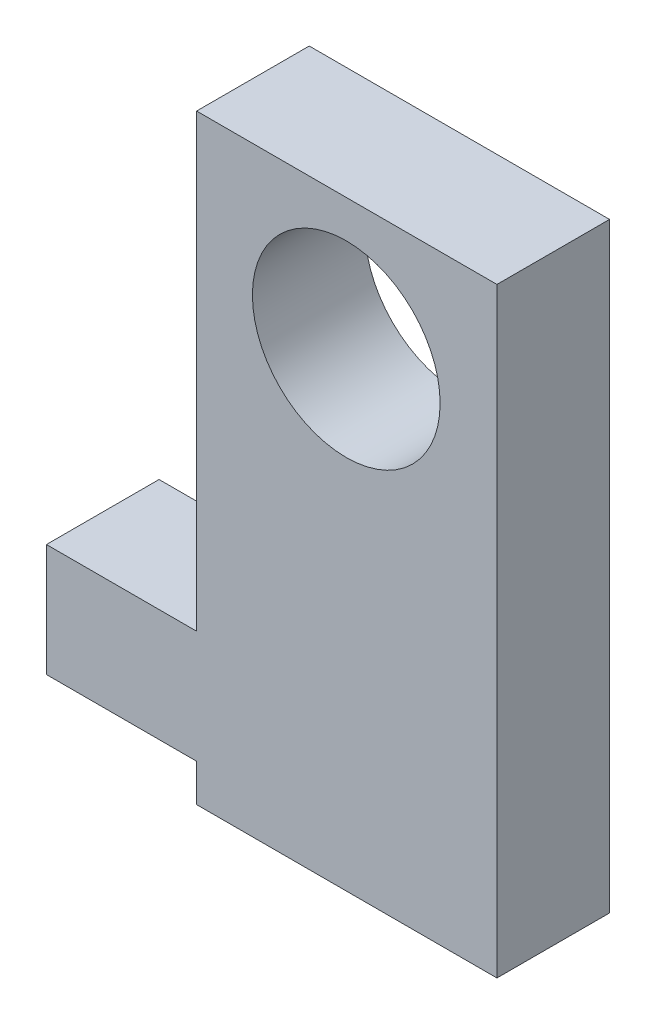
SolidWorks part; units mm, degrees
ref_plane "Front Plane" through (0, 0, 0) normal (0, 0, 1) x (1, 0, 0)
ref_plane "Top Plane" through (0, 0, 0) normal (0, 1, 0) x (1, 0, 0)
ref_plane "Right Plane" through (0, 0, 0) normal (1, 0, 0) x (0, 0, -1)
sketch "Sketch1" plane through (0, 0, 0) normal (0, 0, 1) x (1, 0, 0)
  line L1 (0, 0) -> (8, 0)
  line L2 (0, 0) -> (0, 16)
  line L3 (0, 16) -> (8, 16)
  line L4 (8, 0) -> (8, 16)
  dimension "D1" = 16
  dimension "D2" = 8
extrude "Boss-Extrude1" add sketch "Sketch1" along normal blind 3
sketch "Sketch2" plane through (0, 0, 0) normal (-1, 0, 0) x (0, 0, 1)
  line L0 (0, 0.1348) -> (0, 0.0015) construction
  line L1 (0, 16) -> (0, 0) construction
  line L2 (3, 16) -> (3, 0) construction
  line L7 (0, 1) -> (3, 1)
  line L12 (0, 1) -> (0, 4)
  line L13 (0, 4) -> (3, 4)
  line L14 (3, 1) -> (3, 4)
  line L15 (3, 0) -> (0, 0) construction
  dimension "D1" = 1
  dimension "D2" = 3
sketch "Sketch3" plane through (0, 0, 3) normal (0, 0, 1) x (1, 0, 0)
  line L0 (8, 16) -> (0, 16) construction
  circle A0 centre (3.9865, 12.5) radius 2.5
  dimension "D1" = 5
  dimension "D2" = 3.5
extrude "Cut-Extrude1" cut sketch "Sketch3" against normal blind 10
extrude "Boss-Extrude3" add sketch "Sketch2" along normal blind 4
